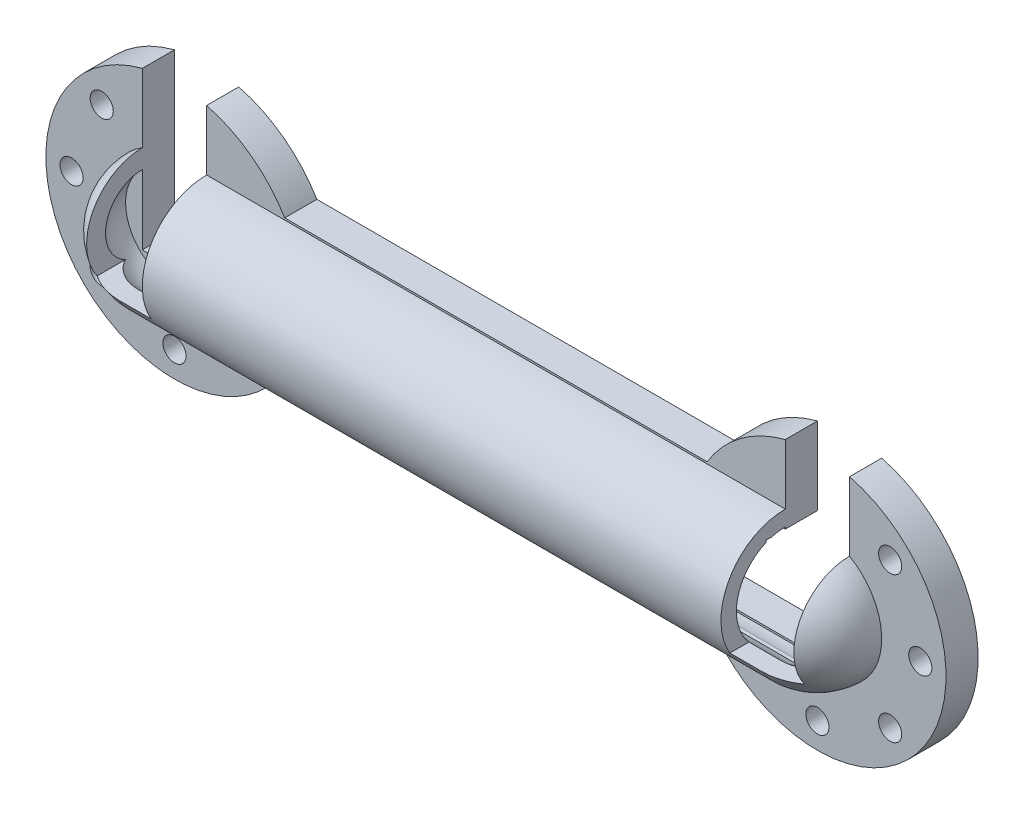
SolidWorks part; units mm, degrees
ref_plane "Plan de face" through (0, 0, 0) normal (0, 0, 1) x (1, 0, 0)
ref_plane "Plan de dessus" through (0, 0, 0) normal (0, 1, 0) x (1, 0, 0)
ref_plane "Plan de droite" through (0, 0, 0) normal (1, 0, 0) x (0, 0, -1)
sketch "Esquisse1" plane through (0, 0, 0) normal (0, 0, 1) x (1, 0, 0)
  line L0 (0, 0) -> (50, 0) construction
  line L1 (0, 5.1477) -> (50, 5.1477)
  line L2 (0, -5.1477) -> (50, -5.1477)
  arc A0 (0, 5.1477) -> (0, -5.1477) centre (0, 0) ccw
  arc A1 (50, -5.1477) -> (50, 5.1477) centre (50, 0) ccw
  circle A2 centre (0, 0) radius 2.45
  circle A3 centre (50, 0) radius 2.45
  point P3 (25, 0)
  dimension "D1" = 50
extrude "Boss.-Extru.1" add sketch "Esquisse1" along normal blind 2.5
sketch "Esquisse4" plane through (0, 0, 2.5) normal (0, 0, 1) x (1, 0, 0)
  circle A0 centre (0, 0) radius 10
  circle A1 centre (0, 0) radius 2.45
  circle A2 centre (50, 0) radius 2.45
  circle A3 centre (50, 0) radius 10
extrude "Boss.-Extru.4" add sketch "Esquisse4" against normal blind 2.5
sketch "Esquisse5" plane through (0, 0, 2.5) normal (0, 0, 1) x (1, 0, 0)
  line L0 (0, 0) -> (-10, 0) construction
  line L1 (25, 5.1477) -> (25, -5.1477) construction
  line L2 (41.4267, 5.1477) -> (8.5733, 5.1477) construction
  line L3 (8.5733, -5.1477) -> (41.4267, -5.1477) construction
  arc A0 (8.5733, 5.1477) -> (8.5733, -5.1477) centre (0, 0) ccw construction
  circle A1 centre (0, 0) radius 8 construction
  circle A2 centre (-8, 0) radius 0.9
  circle A3 centre (-5.6569, 5.6569) radius 0.9
  circle A4 centre (0, 8) radius 0.9
  circle A8 centre (0, -8) radius 0.9
  circle A9 centre (-5.6569, -5.6569) radius 0.9
  circle A13 centre (50, -8) radius 0.9
  circle A14 centre (55.6569, -5.6569) radius 0.9
  circle A15 centre (58, 0) radius 0.9
  circle A16 centre (55.6569, 5.6569) radius 0.9
  circle A17 centre (50, 8) radius 0.9
  circle A18 centre (5.6569, -5.6569) radius 0.9 [skipped]
  circle A19 centre (8, 0) radius 0.9 [skipped]
  circle A20 centre (5.6569, 5.6569) radius 0.9 [skipped]
  point P25 (0, 0)
  dimension "D1" = 8
extrude "Enlèv. mat.-Extru.3" cut sketch "Esquisse5" against normal blind 10
sketch "Esquisse6" plane through (0, 0, 0) normal (0, 1, 0) x (1, 0, 0)
  line L0 (8.5733, -6.3) -> (41.4267, -6.3)
  line L1 (8.5733, 0) -> (41.4267, 0) construction
  line L2 (8.5733, 0) -> (8.5733, -7.5) construction
  line L3 (8.5733, -7.5) -> (41.4267, -7.5)
  line L4 (41.4267, 0) -> (41.4267, -7.5) construction
  line L5 (50, -7.5) -> (41.4267, -7.5)
  line L6 (8.5733, -6.3) -> (0, -6.3)
  line L7 (8.5733, -2.5) -> (41.4267, -2.5) construction
  line L8 (0, -8.4373) -> (0, 0.8589) construction
  line L9 (25, 0) -> (25, -10.5492) construction
  line L10 (0, -6.3) -> (0, -7.5)
  line L11 (0, -7.5) -> (8.5733, -7.5)
  line L12 (50, -6.3) -> (50, -7.5)
  line L13 (41.4267, -6.3) -> (50, -6.3)
  point P7 (25, -7.5)
  point P23 (25, -6.3)
  dimension "D1" = 7.5
  dimension "D2" = 1.2
revolve "Révolution1" add sketch "Esquisse6" angle 90 about L7 other way angle 90
sketch "Esquisse7" plane through (0, 0, 0) normal (-1, 0, 0) x (0, 0, 1)
  line L0 (2.5, -10) -> (2.5, 10) construction
  line L1 (2.5, 5) -> (2.5, 3.8)
  line L2 (2.5, -3.8) -> (2.5, -5)
  line L3 (2.5, 5) -> (2.5, -5) construction
  arc A0 (2.5, 5) -> (2.5, -5) centre (2.5, 0) cw
  arc A1 (2.5, -5) -> (2.5, 5) centre (2.5, 0) ccw construction
  arc A2 (2.5, 3.8) -> (2.5, -3.8) centre (2.5, 0) cw
revolve "Révolution2" add sketch "Esquisse7" angle 90 about L3
sketch "Esquisse8" plane through (50, 0, 0) normal (1, 0, 0) x (0, 0, -1)
  line L0 (-2.5, 5) -> (-2.5, -5) construction
  line L1 (-2.5, 10) -> (-2.5, -10) construction
  line L2 (-2.5, 5) -> (-2.5, 3.8)
  line L3 (-2.5, -3.8) -> (-2.5, -5)
  arc A0 (-2.5, 5) -> (-2.5, -5) centre (-2.5, 0) ccw construction
  arc A2 (-2.5, -5) -> (-2.5, 5) centre (-2.5, 0) cw
  arc A3 (-2.5, -3.8) -> (-2.5, 3.8) centre (-2.5, 0) cw
revolve "Révolution3" add sketch "Esquisse8" angle 90 about L0
sketch "Esquisse9" plane through (0, 0, 0) normal (0, 0, -1) x (-1, 0, 0)
  line L1 (-25, -5.1477) -> (-25, 5.1477) construction
  line L2 (-8.5733, -5.1477) -> (-41.4267, -5.1477) construction
  line L3 (-41.4267, 5.1477) -> (-8.5733, 5.1477) construction
  line L9 (1, -3.6477) -> (-51, -3.6477)
  line L10 (1, -3.6477) -> (1, 3.6477)
  line L11 (1, 3.6477) -> (-51, 3.6477)
  line L12 (-51, -3.6477) -> (-51, 3.6477)
  line L13 (1, -3.6477) -> (-51, 3.6477) construction
  line L14 (1, 3.6477) -> (-51, -3.6477) construction
  point P13 (-25, 0)
  dimension "D1" = 1.5
  dimension "D2" = 26
extrude "Enlèv. mat.-Extru.4" cut sketch "Esquisse9" against normal blind 4
sketch "Esquisse10" plane through (0, 0, 2.5) normal (0, 0, 1) x (1, 0, 0)
  line L0 (0, -5) -> (0, 12.5675) construction
  line L1 (25, 5.1477) -> (25, -7.5249) construction
  line L2 (-2.5, -2.5407) -> (2.5, -2.5407)
  line L3 (-2.5, -2.5407) -> (-2.5, 12.4503)
  line L4 (-2.5, 12.4503) -> (2.5, 12.4503)
  line L5 (2.5, -2.5407) -> (2.5, 12.4503)
  line L6 (-2.5, -2.5407) -> (2.5, 12.4503) construction
  line L7 (-2.5, 12.4503) -> (2.5, -2.5407) construction
  line L8 (41.4267, 5.1477) -> (8.5733, 5.1477) construction
  line L9 (47.5, -2.5407) -> (47.5, 12.4503)
  line L10 (52.5, -2.5407) -> (52.5, 12.4503)
  line L11 (52.5, 12.4503) -> (47.5, 12.4503)
  line L12 (52.5, -2.5407) -> (47.5, -2.5407)
  point P4 (0, 4.9548)
  dimension "D1" = 5
extrude "Enlèv. mat.-Extru.5" cut sketch "Esquisse10" against normal through all and the other way through all
